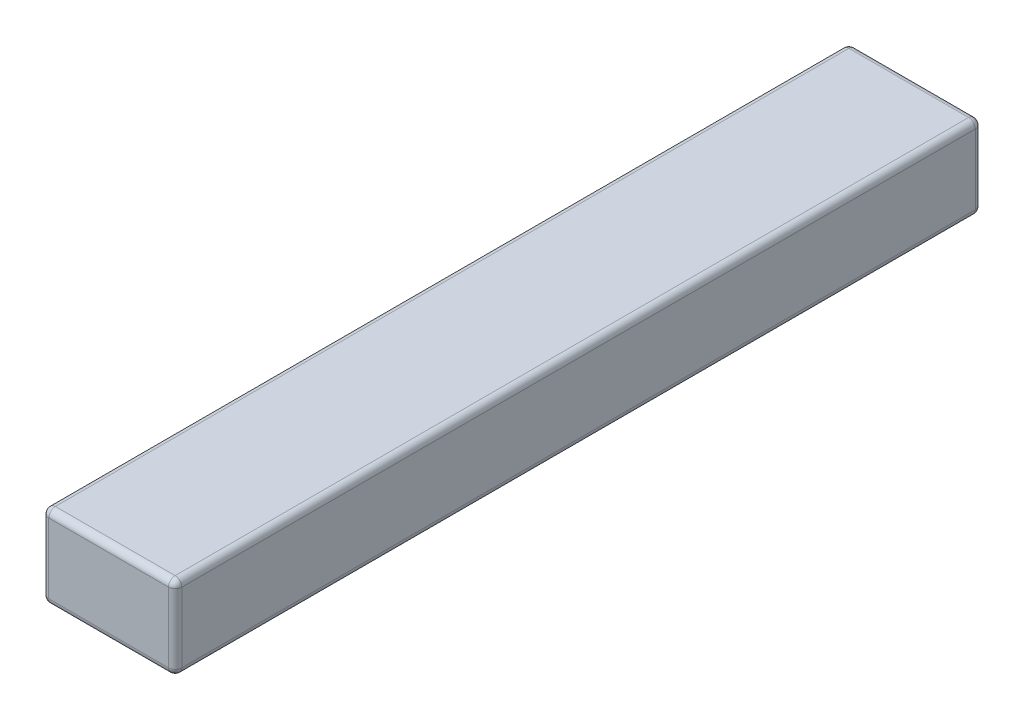
SolidWorks part; units mm, degrees
material "Custom Plastic"
ref_plane "Front Plane" through (0, 0, 0) normal (0, 0, 1) x (1, 0, 0)
ref_plane "Top Plane" through (0, 0, 0) normal (0, 1, 0) x (1, 0, 0)
ref_plane "Right Plane" through (0, 0, 0) normal (1, 0, 0) x (0, 0, -1)
sketch "Sketch1" plane through (0, 0, 0) normal (0, 0, 1) x (1, 0, 0)
  line L1 (0, 0) -> (80, 0)
  line L2 (0, 0) -> (0, -50)
  line L3 (0, -50) -> (80, -50)
  line L4 (80, 0) -> (80, -50)
  dimension "D1" = 50
  dimension "D2" = 80
extrude "Boss-Extrude1" add sketch "Sketch1" along normal blind 485
fillet "Fillet1" radius 4 12 edges at (0, -25, 485) (0, -25, 0) (0, -50, 242.5) (40, -50, 485) (40, -50, 0) (80, -50, 242.5) (80, -25, 485) (80, -25, 0) (80, 0, 242.5) (40, 0, 485) (0, 0, 242.5) (40, 0, 0)
